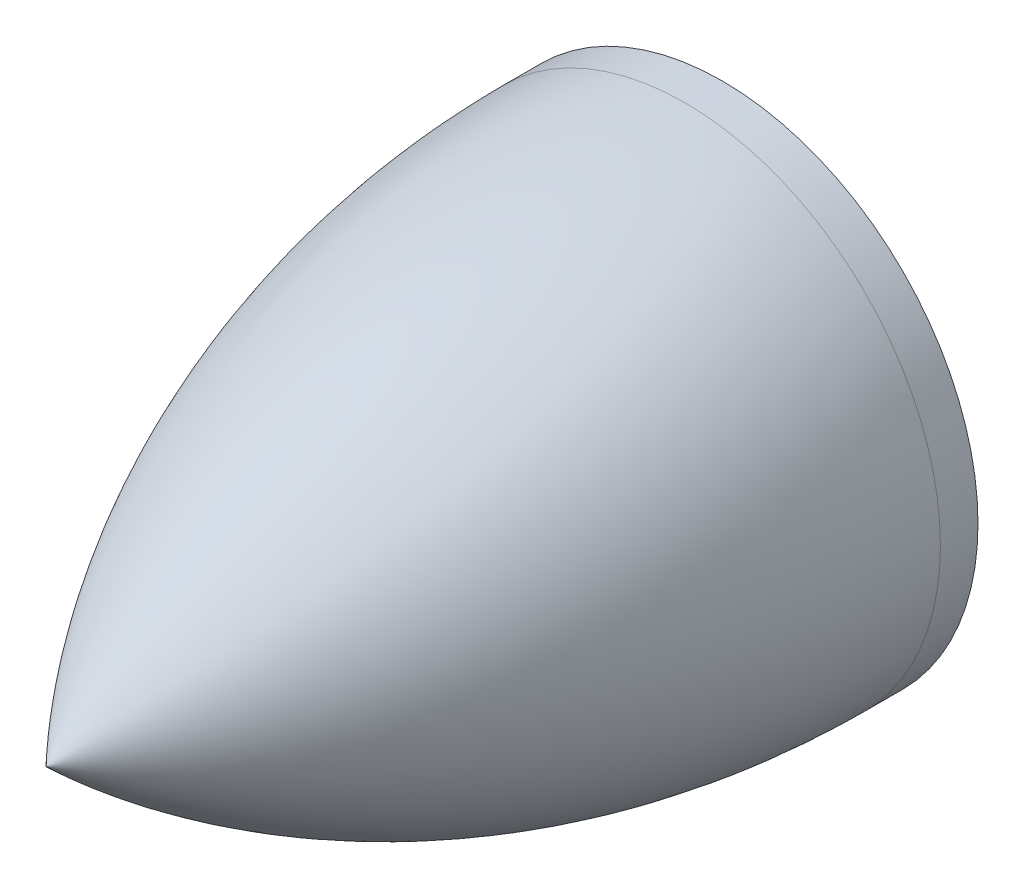
SolidWorks part; units mm, degrees
material "PVC 0.007 Plasticized"
ref_plane "Front Plane" through (0, 0, 0) normal (0, 0, 1) x (1, 0, 0)
ref_plane "Top Plane" through (0, 0, 0) normal (0, 1, 0) x (1, 0, 0)
ref_plane "Right Plane" through (0, 0, 0) normal (1, 0, 0) x (0, 0, -1)
sketch "Sketch2" plane through (0, 0, 0) normal (1, 0, 0) x (0, 0, -1)
  line L0 (0, 178.5) -> (0, 246.5)
  line L1 (-170, 178.5) -> (0, 178.5)
  line L2 (-397.7647, 178.5) -> (0, 178.5) construction
  line L3 (0, 246.5) -> (0, 241.5)
  line L4 (-170, 178.5) -> (-165, 178.5)
  arc A1 (0, 246.5) -> (-170, 178.5) centre (0, 0) ccw
  arc A2 (0, 241.5) -> (-162.6653, 178.5) centre (0, 0) ccw
  arc A3 (0, 241.5) -> (-166.5517, 174.8793) centre (0, 0) ccw construction
  dimension "D1" = 170
  dimension "D3" = 397.7647
  dimension "D2" = 68
  dimension "D4" = 5
  dimension "D5" = 5
  dimension "D6" = 5
revolve "Revolve1" add sketch "Sketch2" angle 360 about L2
sketch "Sketch3" plane through (0, 0, 0) normal (0, 0, -1) x (-1, 0, 0)
  circle A0 centre (0, 178.5) radius 68
  circle A1 centre (0, 178.5) radius 68 construction
  circle A2 centre (0, 178.5) radius 63
  circle A3 centre (0, 178.5) radius 63 construction
  circle A4 centre (0, 178.5) radius 66.25
  circle M2 centre (0, 178.5) radius 68
  dimension "D1" = 1.75
extrude "Boss-Extrude1" add sketch "Sketch3" along normal blind 10 contours A4 M2
